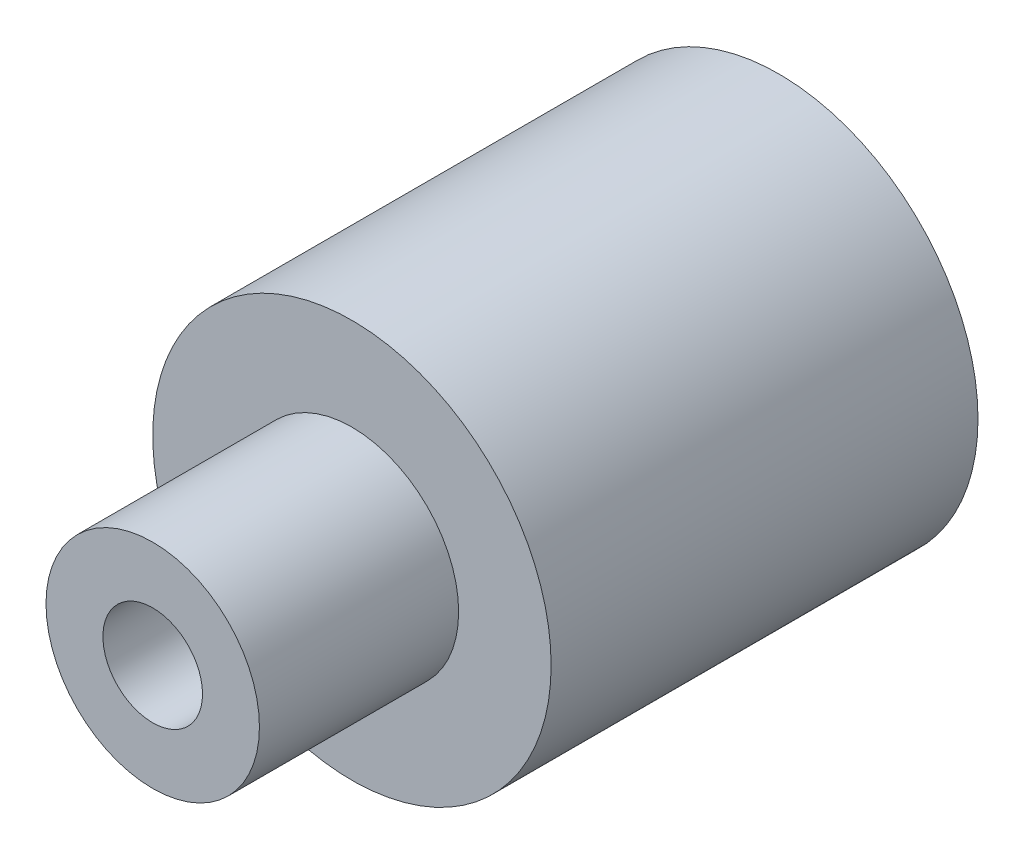
SolidWorks part; units mm, degrees
ref_plane "Front Plane" through (0, 0, 0) normal (1, 0, 0) x (0, 1, 0)
ref_plane "Top Plane" through (0, 0, 0) normal (0, 0, 1) x (0, 1, 0)
ref_plane "Right Plane" through (0, 0, 0) normal (0, 1, 0) x (-1, 0, 0)
sketch "Sketch1" plane through (0, 0, 0) normal (0, 0, 1) x (0, 1, 0)
  circle A0 centre (0, 0) radius 7
  dimension "D1" = 14
extrude "Boss-Extrude1" add sketch "Sketch1" along normal blind 15 contours A0
sketch "Sketch2" plane through (0, 0, 15) normal (0, 0, 1) x (1, 0, 0)
  circle A0 centre (0, 0) radius 3.75
  dimension "D1" = 7.5
extrude "Boss-Extrude2" add sketch "Sketch2" along normal blind 7
sketch "Sketch3" plane through (0, 0, 22) normal (0, 0, 1) x (1, 0, 0)
  circle A0 centre (0, 0) radius 1.75
  dimension "D1" = 3.5
extrude "Cut-Extrude1" cut sketch "Sketch3" against normal up to surface (22 mm away) contours A0 up to face at (7, 0, 0)
